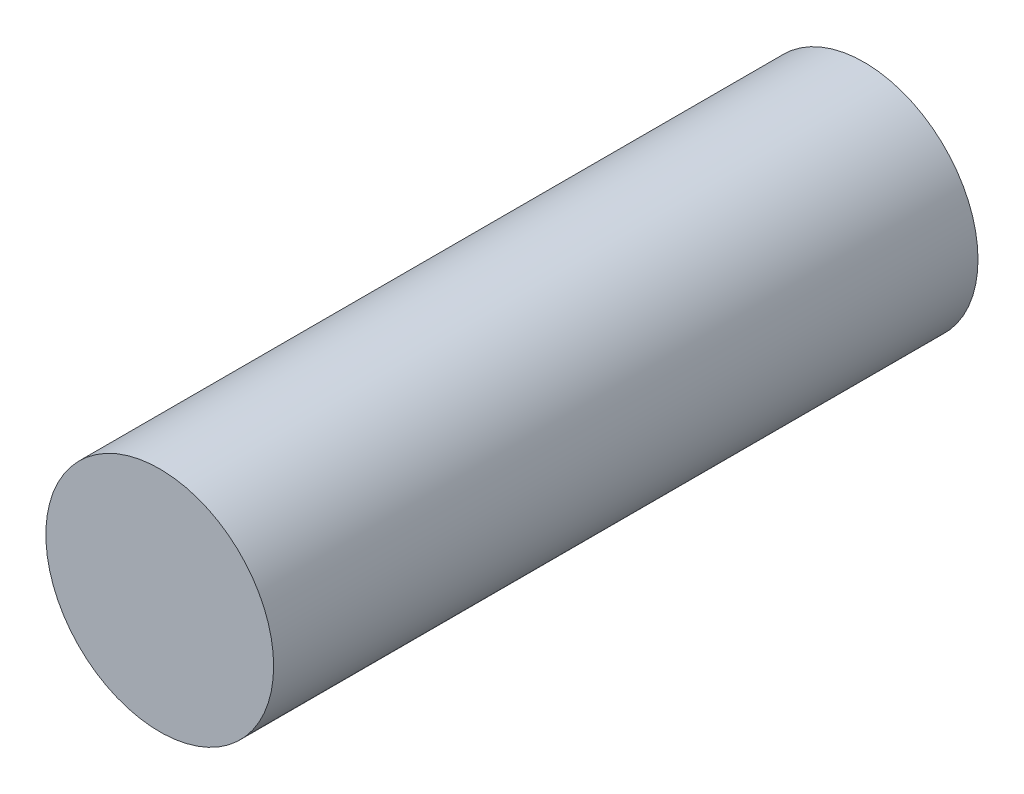
SolidWorks part; units mm, degrees
ref_plane "前视基准面" through (0, 0, 0) normal (0, 0, 1) x (1, 0, 0)
ref_plane "上视基准面" through (0, 0, 0) normal (0, 1, 0) x (1, 0, 0)
ref_plane "右视基准面" through (0, 0, 0) normal (1, 0, 0) x (0, 0, -1)
other "Configuration Table"
sketch "草图1" plane through (0, 0, 0) normal (0, 0, 1) x (1, 0, 0)
  circle A0 centre (0, 0) radius 3.8
  dimension "diameter" = 7.6
extrude "Cable" add sketch "草图1" along normal blind 23.5
